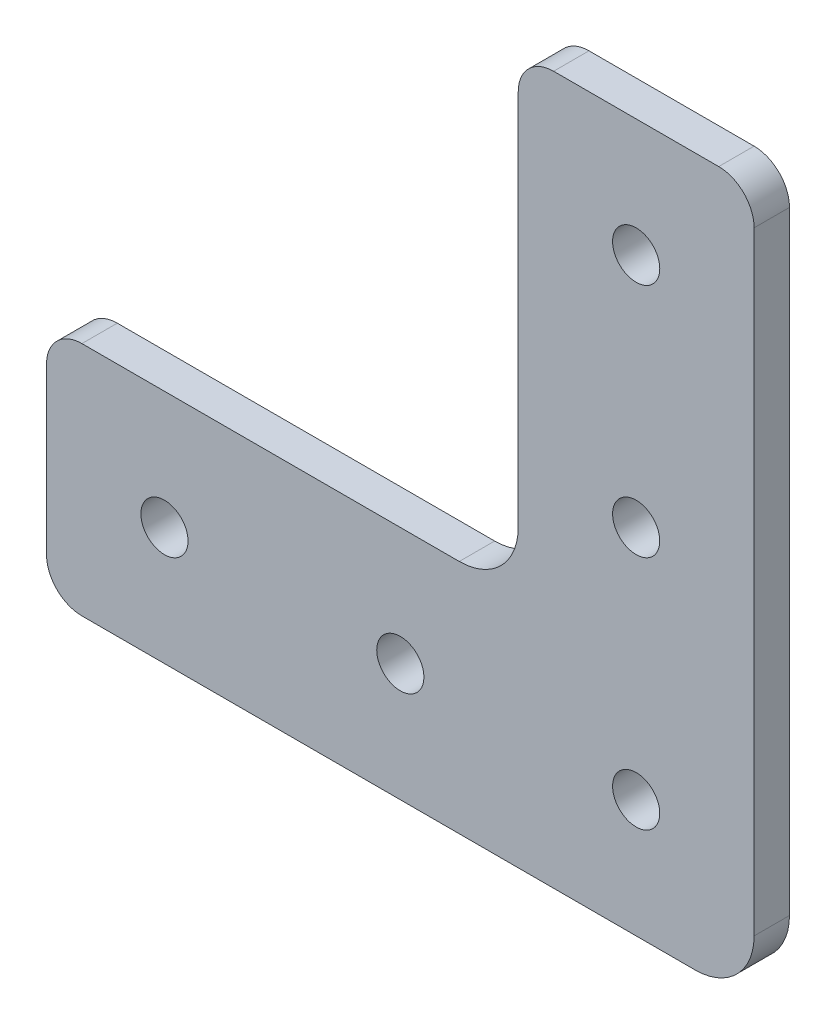
SolidWorks part; units mm, degrees
material "Thornel Mat VMA"
ref_plane "前视基准面" through (0, 0, 0) normal (0, 0, 1) x (1, 0, 0)
ref_plane "上视基准面" through (0, 0, 0) normal (0, 1, 0) x (1, 0, 0)
ref_plane "右视基准面" through (0, 0, 0) normal (1, 0, 0) x (0, 0, -1)
other "Configuration Table"
sketch "草图1" plane through (0, 0, 0) normal (0, 0, 1) x (1, 0, 0)
  line L1 (0, 0) -> (20, 0)
  line L2 (0, 0) -> (0, 60)
  line L3 (0, 60) -> (20, 60)
  line L4 (20, 0) -> (20, 60)
  dimension "D1" = 60
  dimension "D2" = 20
extrude "凸台-拉伸1" add sketch "草图1" along normal blind 3
sketch "草图2" plane through (0, 0, 3) normal (0, 0, 1) x (1, 0, 0)
  line L1 (20, 0) -> (-40, 0)
  line L2 (20, 0) -> (20, 20)
  line L3 (20, 20) -> (-40, 20)
  line L4 (-40, 0) -> (-40, 20)
  dimension "D1" = 20
  dimension "D2" = 60
extrude "凸台-拉伸2" add sketch "草图2" against normal blind 3
sketch "草图3" plane through (0, 0, 3) normal (0, 0, 1) x (1, 0, 0)
  line L0 (0, 20) -> (20, 0) construction
  line L1 (10, 60) -> (10, 10) construction
  line L2 (20, 60) -> (0, 60) construction
  line L3 (10, 10) -> (-40, 10) construction
  line L4 (-40, 20) -> (-40, 0) construction
  circle A0 centre (10, 10) radius 2
  circle A1 centre (10, 30) radius 2
  circle A2 centre (10, 50) radius 2
  circle A4 centre (-10, 10) radius 2
  circle A5 centre (-30, 10) radius 2
  dimension "D1" = 4
  dimension "D3" = 20
  dimension "D2" = 3
extrude "切除-拉伸1" cut sketch "草图3" against normal blind 3
fillet "圆角3" radius 5 2 edges at (20, 0, 1.5) (0, 20, 1.5)
fillet "圆角2" radius 3 4 edges at (-40, 0, 1.5) (-40, 20, 1.5) (20, 60, 1.5) (0, 60, 1.5)
